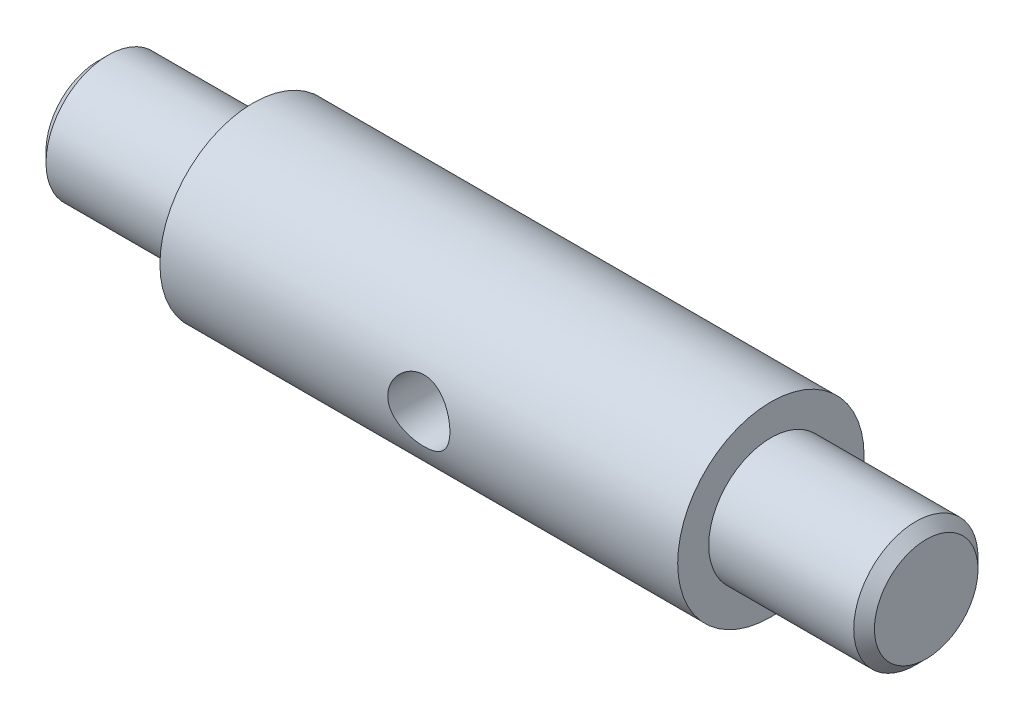
SolidWorks part; units mm, degrees
ref_plane "Front Plane" through (0, 0, 0) normal (0, 0, 1) x (1, 0, 0)
ref_plane "Top Plane" through (0, 0, 0) normal (0, 1, 0) x (1, 0, 0)
ref_plane "Right Plane" through (0, 0, 0) normal (1, 0, 0) x (0, 0, -1)
sketch "Sketch1" plane through (0, 0, 0) normal (0, 0, 1) x (1, 0, 0)
  line L0 (0, 0) -> (25776.9348, 0) construction
  line L1 (-40, 0) -> (-40, 6)
  line L2 (-40, 6) -> (-25, 6)
  line L3 (-25, 6) -> (-25, 9)
  line L4 (-25, 9) -> (25, 9)
  line L5 (25, 9) -> (25, 6)
  line L6 (25, 6) -> (40, 6)
  line L7 (40, 6) -> (40, 0)
  line L8 (0, 0) -> (0, -25776.9348) construction
  line L9 (-40, 0) -> (40, 0)
  dimension "D1" = 15
  dimension "D2" = 50
  dimension "D3" = 12
  dimension "D4" = 18
revolve "Revolve1" add sketch "Sketch1" angle 360 about L0
sketch "Sketch2" plane through (0, 0, 0) normal (0, 0, 1) x (1, 0, 0)
  circle A0 centre (0, 0) radius 3
  dimension "D1" = 6
extrude "Cut-Extrude1" cut sketch "Sketch2" against normal through all both and the other way through all
hole_wizard "Ø6.0mm Dowel Hole1" positions "Sketch3" profile "Sketch4" hole size "Ø6.0" standard "ISO"
sketch "Sketch3" plane through (-40, 0, 0) normal (-1, 0, 0) x (0, 0, 1)
  point P0 (0, 0)
sketch "Sketch4" plane through (-40, 0, 0) normal (0, 1, 0) x (0, 0, 1)
  line L0 (0, 0) -> (0, 46.7321)
  line L1 (0, 46.7321) -> (3, 45)
  line L2 (3, 45) -> (3, 0)
  line L5 (3, 0) -> (0, 0)
  line L10 (0, 46.7321) -> (-3, 45) construction
  line L11 (0, -6.35) -> (0, 107.95) construction
  dimension "Hole Dia." = 6
  dimension "Hole Depth" = 45
  dimension "Drill Angle" = 120
chamfer "Chamfer1" distance 1 angle 45 2 edges at (40, 0, 6) (-40, 0, 6)
